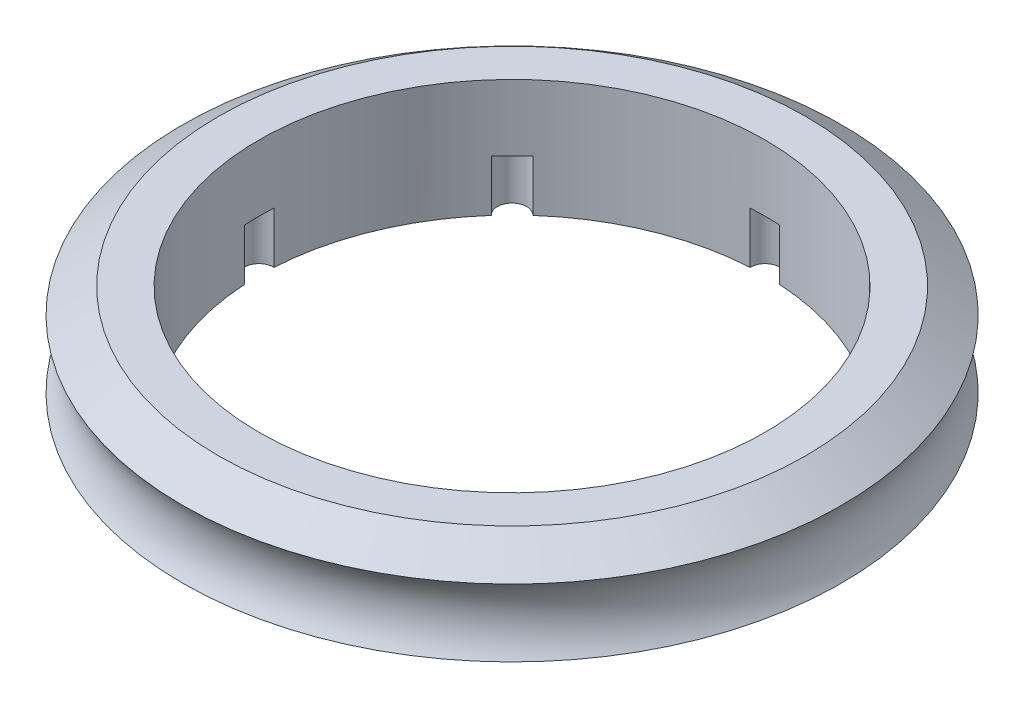
SolidWorks part; units mm, degrees
ref_plane "Front Plane" through (0, 0, 0) normal (0, 0, 1) x (1, 0, 0)
ref_plane "Top Plane" through (0, 0, 0) normal (0, 1, 0) x (1, 0, 0)
ref_plane "Right Plane" through (0, 0, 0) normal (1, 0, 0) x (0, 0, -1)
sketch "Sketch1" plane through (0, 0, 0) normal (0, 1, 0) x (1, 0, 0)
  circle A0 centre (0, 0) radius 68.94 construction
  dimension "D1" = 137.88
sketch "Sketch2" plane through (0, 0, 0) normal (1, 0, 0) x (0, 0, -1)
  line L0 (68.94, 0) -> (68.94, 32)
  line L1 (68.94, 0) -> (-68.94, 0) construction
  line L2 (68.94, 32) -> (80, 32)
  line L3 (80, 32) -> (89.7439, 25.1772)
  line L4 (89.7439, 6.8228) -> (80, 0)
  line L5 (80, 0) -> (68.94, 0)
  line L6 (68.94, 16) -> (86.8504, 16) construction
  line L7 (89.7439, 25.1772) -> (102.8504, 16) construction
  line L8 (102.8504, 16) -> (89.7439, 6.8228) construction
  line L9 (0, 24.7733) -> (0, -25.9476) construction
  arc A0 (89.7439, 25.1772) -> (89.7439, 6.8228) centre (102.8504, 16) ccw
  dimension "D5" = 16
  dimension "D1" = 32
  dimension "D2" = 11.06
  dimension "D3" = 70
  dimension "D4" = 68.94
revolve "Revolve1" add sketch "Sketch2" angle 360 about L9
sketch "Sketch3" plane through (0, 0, 0) normal (0, 1, 0) x (1, 0, 0)
  circle A0 centre (0, 0) radius 68.94 construction
  circle A1 centre (0, 0) radius 68.94 construction
  circle A2 centre (0, 68.94) radius 4
  circle A3 centre (0, 0) radius 68.94 construction
  circle A4 centre (48.7479, 48.7479) radius 4
  circle A5 centre (0, 0) radius 68.94 construction
  circle A6 centre (68.94, 0) radius 4
  circle A7 centre (0, 0) radius 68.94 construction
  circle A8 centre (48.7479, -48.7479) radius 4
  circle A9 centre (0, 0) radius 68.94 construction
  circle A10 centre (0, -68.94) radius 4
  circle A11 centre (0, 0) radius 68.94 construction
  circle A12 centre (-48.7479, -48.7479) radius 4
  circle A13 centre (0, 0) radius 68.94 construction
  circle A14 centre (-68.94, 0) radius 4
  circle A15 centre (0, 0) radius 68.94 construction
  circle A16 centre (-48.7479, 48.7479) radius 4
  point P29 (0, 0)
  dimension "D1" = 8
  dimension "D2" = 8
extrude "Cut-Extrude1" cut sketch "Sketch3" along normal blind 14
